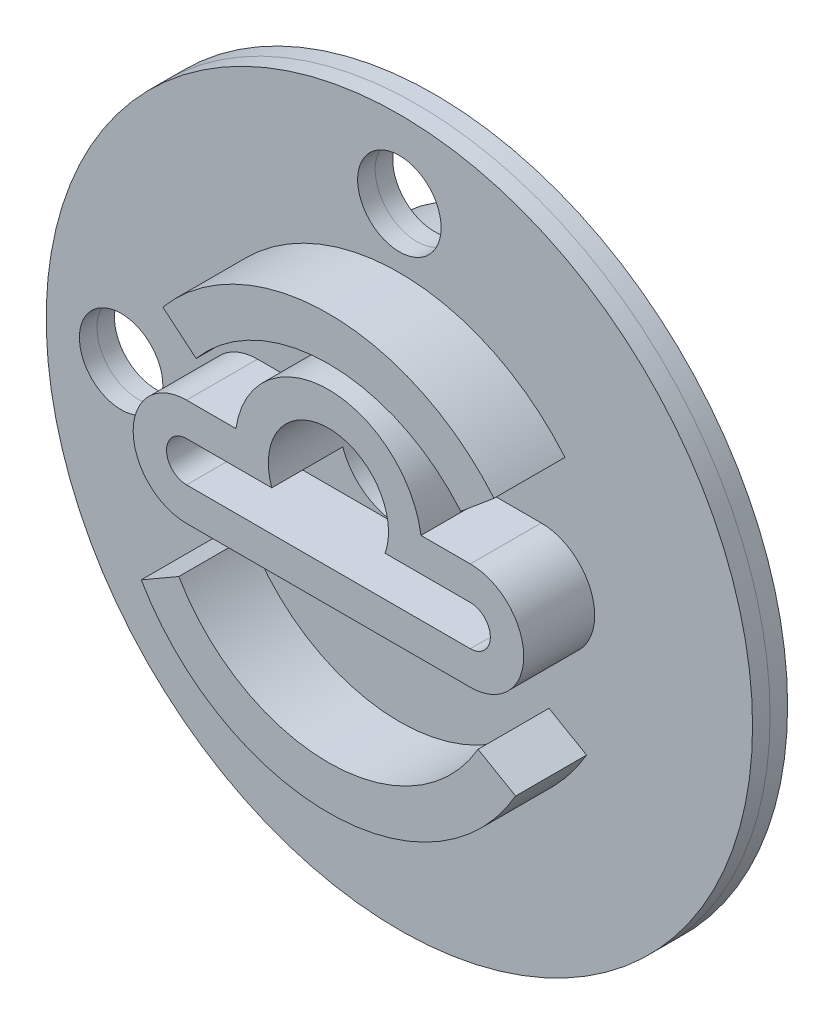
SolidWorks part; units mm, degrees
ref_plane "Front Plane" through (0, 0, 0) normal (0, 0, 1) x (1, 0, 0)
ref_plane "Top Plane" through (0, 0, 0) normal (0, 1, 0) x (1, 0, 0)
ref_plane "Right Plane" through (0, 0, 0) normal (1, 0, 0) x (0, 0, -1)
sketch "Sketch1" plane through (0, 0, 0) normal (0, 0, 1) x (1, 0, 0)
  line L0 (0, 29.8051) -> (0, -31.034) construction
  line L1 (0, 21.16) -> (30.3616, 21.16) construction
  line L2 (0, 10.425) -> (27.4702, 10.425) construction
  line L7 (0, 7.983) -> (0, -1.8885) construction
  circle A0 centre (0, 0) radius 21.16
  point P10 (-7.5124, 8.4374)
  point P12 (9.4132, 9.0185)
  point P13 (7.5124, 8.4374)
  point P25 (-3.5248, 8.4374)
  point P28 (-7.5124, 8.4374)
  point P29 (11.5, 8.4374)
  point P31 (-5.6117, 9.0185)
  point P32 (7.5124, 8.4374)
  dimension "D3" = 42.32
extrude "Boss-Extrude2" add sketch "Sketch1" along normal blind 2.1
sketch "Sketch3" plane through (0, 0, 2.1) normal (0, 0, 1) x (1, 0, 0)
  line L0 (0, 23.901) -> (0, 17.4278) construction
  line L1 (0, 21.16) -> (22.4833, 21.16) construction
  line L2 (0, 7.01) -> (23.6909, 7.01) construction
  circle A1 centre (0, 3.41) radius 3.6
  circle A2 centre (0, 0) radius 21.16 construction
  dimension "D1" = 7.2
  dimension "D2" = 14.15
extrude "Cut-Extrude1" cut sketch "Sketch3" against normal through all and the other way through all
sketch "Sketch6" plane through (0, 0, 0) normal (0, 0, -1) x (-1, 0, 0)
  circle A2 centre (0, 3.595) radius 4.85
  circle A6 centre (0, 3.41) radius 3.6
  circle A7 centre (0, 3.41) radius 3.6
  dimension "D2" = 0
  dimension "D1" = 9.7
extrude "Boss-Extrude5" add sketch "Sketch6" along normal blind 2.2
sketch "Sketch7" plane through (0, 0, 0) normal (0, 0, -1) x (-1, 0, 0)
  circle A0 centre (0, 0) radius 10
  circle A1 centre (0, 0) radius 11.25
  dimension "D1" = 20
  dimension "D2" = 22.5
extrude "Boss-Extrude6" add sketch "Sketch7" along normal blind 6
sketch "Sketch8" plane through (0, 0, 0) normal (1, 0, 0) x (0, 0, -1)
  line L0 (-1.05, 21.16) -> (-1.05, -21.16)
  line L1 (0, 21.16) -> (-2.1, 21.16) construction
  line L2 (-2.1, -21.16) -> (0, -21.16) construction
split "Split1" trim tools "Sketch8" bodies to split 109 resulting bodies 110 111
sketch "Sketch9" plane through (0, 0, 2.1) normal (0, 0, 1) x (1, 0, 0)
  line L0 (0, 24.1336) -> (0, -27.3818) construction
  line L1 (-9.7, -0.443) -> (-9.7, 3.9046) construction
  line L2 (9.7, -0.443) -> (9.7, 5.0091) construction
  line L3 (-8.5, -0.19) -> (8.5, -0.19)
  line L4 (0, -0.19) -> (14.2995, -0.19) construction
  line L5 (-8.5, -2.19) -> (8.5, -2.19)
  line L6 (-8.5, 4.21) -> (-5.5426, 4.21)
  line L7 (-8.5, 2.21) -> (-3.3941, 2.21)
  line L8 (5.5426, 4.21) -> (8.5, 4.21)
  line L9 (3.3941, 2.21) -> (8.5, 2.21)
  arc A0 (-8.5, 2.21) -> (-8.5, -0.19) centre (-8.5, 1.01) ccw
  arc A1 (8.5, -0.19) -> (8.5, 2.21) centre (8.5, 1.01) ccw
  circle A2 centre (0, 3.41) radius 3.6 construction
  arc A3 (-8.5, 4.21) -> (-8.5, -2.19) centre (-8.5, 1.01) ccw
  arc A5 (8.5, -2.19) -> (8.5, 4.21) centre (8.5, 1.01) ccw
  circle A6 centre (-8.5, 1.01) radius 1.2 construction
  arc A8 (5.5426, 4.21) -> (-5.5426, 4.21) centre (0, 3.41) ccw
  circle A9 centre (-8.5, 1.01) radius 3.2 construction
  circle A10 centre (8.5, 1.01) radius 3.2 construction
  circle A11 centre (8.5, 1.01) radius 1.2 construction
  circle A13 centre (0, 3.41) radius 3.6
  arc A14 (3.3941, 2.21) -> (-3.3941, 2.21) centre (0, 3.41) ccw
  point P3 (-7.3524, 1.3608)
  point P18 (11.7, 1.01)
  point P20 (9.6476, 1.3608)
  point P31 (-5.3, 1.01)
  dimension "D1" = 2.4
  dimension "D2" = 19.4
  dimension "D3" = 2
  dimension "D4" = 0
  dimension "D5" = 2
extrude "Boss-Extrude7" add sketch "Sketch9" along normal blind 4.25
sketch "Sketch5" plane through (0, 0, 2.1) normal (0, 0, 1) x (1, 0, 0)
  line L2 (0, 0) -> (0, 14.2168) construction
  line L5 (7.9286, 6.6529) -> (9.9203, 8.3241)
  line L6 (-7.9286, 6.6529) -> (-9.9203, 8.3241)
  line L7 (-8.9634, -5.175) -> (-11.215, -6.475)
  line L8 (8.9634, -5.175) -> (11.215, -6.475)
  arc A2 (-8.9634, -5.175) -> (8.9634, -5.175) centre (0, 0) ccw
  arc A3 (7.9286, 6.6529) -> (-7.9286, 6.6529) centre (0, 0) ccw
  circle A4 centre (0, 0) radius 10.35 construction
  arc A5 (-11.215, -6.475) -> (11.215, -6.475) centre (0, 0) ccw
  circle A6 centre (0, 0) radius 12.95 construction
  arc A7 (9.9203, 8.3241) -> (-9.9203, 8.3241) centre (0, 0) ccw
  point P3 (0, 0)
  point P4 (9.8978, 3.026)
  point P5 (12.95, 0)
  point P6 (12.95, 0)
  point P13 (9.8978, 3.026)
  dimension "D1" = 100
  dimension "D5" = 20.7
  dimension "D3" = 120
  dimension "D4" = 60
  dimension "D2" = 50
  dimension "D6" = 2.6
extrude "Boss-Extrude4" add sketch "Sketch5" along normal blind 4.25
sketch "Sketch10" plane through (0, 0, 2.1) normal (0, 0, 1) x (1, 0, 0)
  line L0 (0, 0) -> (-28.718, 0) construction
  line L1 (0, 0) -> (0, 22.4733) construction
  circle A0 centre (0, 16.5276) radius 2.5
  circle A1 centre (-16.6705, 0) radius 2.5
  dimension "D1" = 5
  dimension "D2" = 5
extrude "Cut-Extrude2" cut sketch "Sketch10" against normal through all
